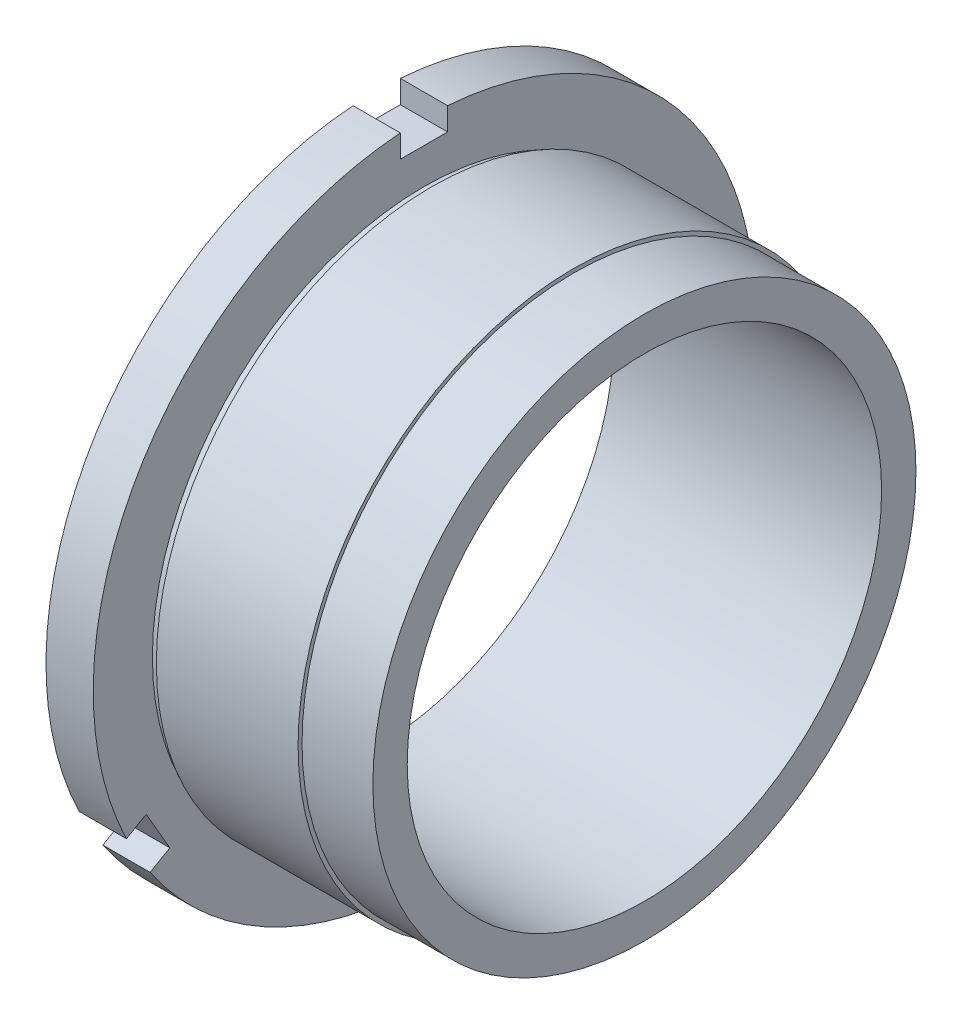
SolidWorks part; units mm, degrees
material "Low Carbon Steel"
ref_plane "Front Plane" through (0, 0, 0) normal (0, 0, 1) x (1, 0, 0)
ref_plane "Top Plane" through (0, 0, 0) normal (0, 1, 0) x (1, 0, 0)
ref_plane "Right Plane" through (0, 0, 0) normal (1, 0, 0) x (0, 0, -1)
sketch "Sketch1" plane through (0, 0, 0) normal (0, 0, 1) x (1, 0, 0)
  line L0 (0, 0) -> (-46.5579, 0) construction
  line L1 (0, 30.125) -> (0, 42)
  line L2 (0, 42) -> (6, 42)
  line L3 (6, 42) -> (6, 34.485)
  line L4 (7, 34.985) -> (25, 34.985)
  line L5 (34, 34.485) -> (34, 30.125)
  line L6 (34, 30.125) -> (0, 30.125)
  line L7 (7, 34.985) -> (7, 34.485)
  line L8 (7, 34.485) -> (6, 34.485)
  line L9 (34, 34.485) -> (25, 34.485)
  line L10 (25, 34.485) -> (25, 34.985)
  dimension "D1" = 6
  dimension "D2" = 34
  dimension "D3" = 60.25
  dimension "D4" = 84
  dimension "D5" = 69.97
  dimension "D6" = 1
  dimension "D7" = 0.5
  dimension "D8" = 9
revolve "Revolve1" add sketch "Sketch1" angle 360 about L0
cosmetic thread "Cosmetic Thread1" parameters "D2"=69
sketch "Sketch2" plane through (0, 0, 0) normal (-1, 0, 0) x (0, 0, 1)
  line L1 (-3, 44.2168) -> (3, 44.2168)
  line L2 (-3, 44.2168) -> (-3, 39)
  line L3 (-3, 39) -> (3, 39)
  line L4 (3, 44.2168) -> (3, 39)
  circle A1 centre (0, 0) radius 42 construction
  point P4 (-3, 41.6084)
  dimension "D1" = 6
  dimension "D2" = 3
  dimension "D3" = 3
extrude "Cut-Extrude1" cut sketch "Sketch2" against normal through all
pattern_circular "CirPattern1" count 3 over 360 about axis through (0, 0, 0) along (1, 0, 0) of "Cut-Extrude1"
